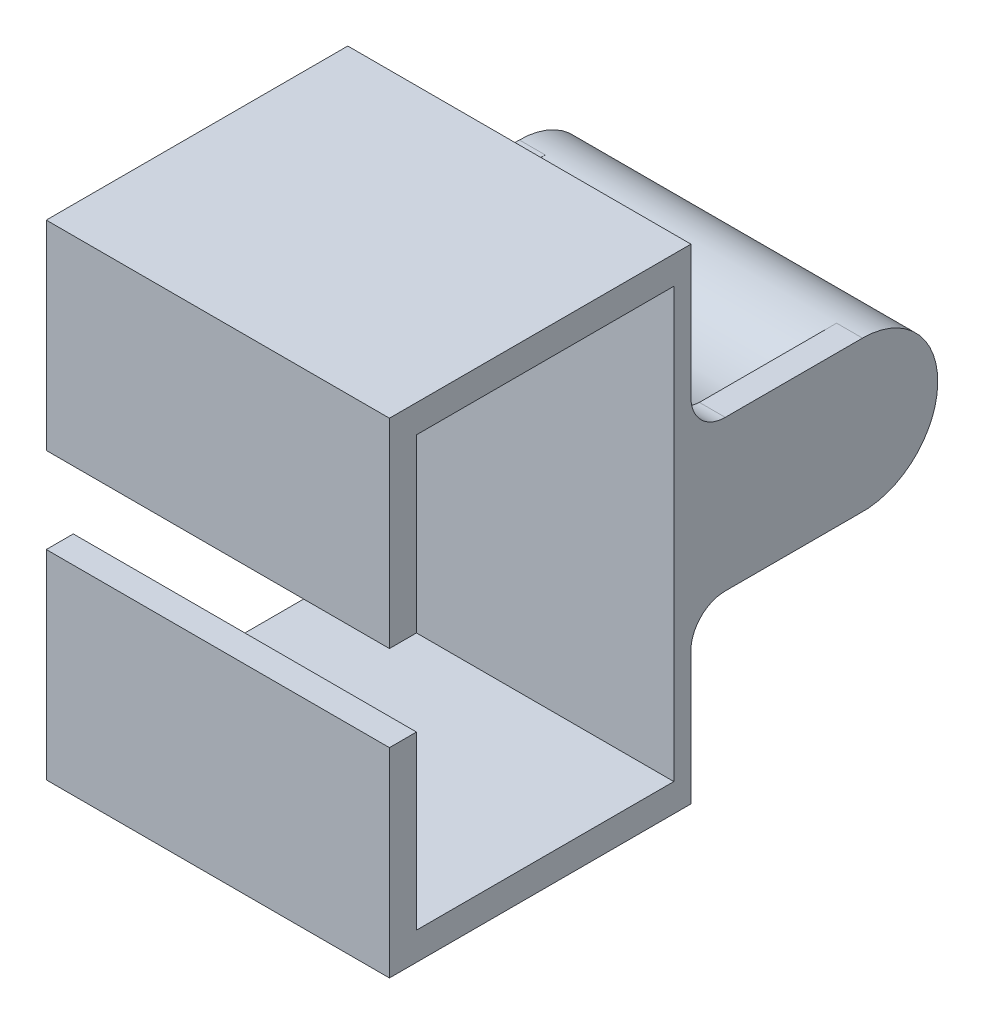
SolidWorks part; units mm, degrees
material "ASTM A36 Steel"
ref_plane "Front Plane" through (0, 0, 0) normal (1, 0, 0) x (0, 1, 0)
ref_plane "Top Plane" through (0, 0, 0) normal (0, 0, 1) x (0, 1, 0)
ref_plane "Right Plane" through (0, 0, 0) normal (0, 1, 0) x (-1, 0, 0)
sketch "Sketch1" plane through (0, 0, 0) normal (1, 0, 0) x (0, 1, 0)
  circle A0 centre (0, 0) radius 11.1361
  dimension "D1" = 22.2722
extrude "Boss-Extrude1" add sketch "Sketch1" along normal blind 50.8 contours A0
sketch "Sketch2" plane through (0, 0, 0) normal (-1, 0, 0) x (0, -1, 0)
  line L0 (12.2437, 0) -> (-12.2437, 0) construction
  line L1 (-11.1361, 0) -> (11.1252, 0)
  line L2 (-11.1361, 0) -> (-11.1361, 25.4)
  line L3 (-11.1361, 25.4) -> (11.1252, 25.4)
  line L4 (11.1252, 0) -> (11.1252, 25.4)
  circle A0 centre (0, 0) radius 11.1361 construction
  dimension "D1" = 25.4
extrude "Boss-Extrude2" add sketch "Sketch2" against normal blind 3.8346 contours L2 L3 L4 L1
sketch "Sketch3" plane through (0, 0, 0) normal (1, 0, 0) x (0, 1, 0)
  line L0 (0, -27.94) -> (0, 27.94) construction
  line L1 (-31.75, 25.4) -> (31.75, 25.4)
  line L2 (-31.75, 25.4) -> (-31.75, 27.9309)
  line L3 (-31.75, 27.9309) -> (31.75, 27.9309)
  line L4 (31.75, 25.4) -> (31.75, 27.9309)
  line L5 (11.1361, 25.4) -> (-11.1252, 25.4) construction
  point P4 (0, 25.4)
  dimension "D1" = 63.5
  dimension "D2" = 2.5309
extrude "Boss-Extrude3" add sketch "Sketch3" along normal blind 50.8
sketch "Sketch4" plane through (0, 0, 0) normal (1, 0, 0) x (0, 1, 0)
  line L0 (31.75, 27.9309) -> (-31.75, 27.9309) construction
  line L1 (-31.75, 25.4) -> (-35.8829, 25.4)
  line L2 (-31.75, 25.4) -> (-31.75, 66.0309)
  line L3 (-31.75, 66.0309) -> (-35.8829, 66.0309)
  line L4 (-35.8829, 25.4) -> (-35.8829, 66.0309)
  line L5 (31.75, 25.4) -> (35.8829, 25.4)
  line L6 (31.75, 25.4) -> (31.75, 66.0309)
  line L7 (31.75, 66.0309) -> (35.8829, 66.0309)
  line L8 (35.8829, 25.4) -> (35.8829, 66.0309)
  dimension "D2" = 38.1
extrude "Boss-Extrude4" add sketch "Sketch4" along normal blind 50.8
sketch "Sketch5" plane through (0, 0, 0) normal (1, 0, 0) x (0, 1, 0)
  line L1 (-35.8829, 66.0309) -> (-6.35, 66.0309)
  line L2 (-35.8829, 66.0309) -> (-35.8829, 70.0326)
  line L3 (-35.8829, 70.0326) -> (-6.35, 70.0326)
  line L4 (-6.35, 66.0309) -> (-6.35, 70.0326)
  line L5 (35.8829, 66.0309) -> (6.35, 66.0309)
  line L6 (35.8829, 66.0309) -> (35.8829, 70.0326)
  line L7 (35.8829, 70.0326) -> (6.35, 70.0326)
  line L8 (6.35, 66.0309) -> (6.35, 70.0326)
  dimension "D2" = 25.4
  dimension "D3" = 12.7
extrude "Boss-Extrude5" add sketch "Sketch5" along normal blind 50.8
sketch "Sketch6" plane through (50.8, 0, 0) normal (1, 0, 0) x (0, 1, 0)
  line L0 (27.94, 0) -> (-27.94, 0) construction
  line L1 (-11.1252, 25.4) -> (11.1361, 25.4)
  line L2 (-11.1252, 25.4) -> (-11.1252, 0)
  line L3 (-11.1252, 0) -> (11.1361, 0)
  line L4 (11.1361, 25.4) -> (11.1361, 0)
  arc A0 (11.1361, 0) -> (-11.1252, 0.4931) centre (0, 0) ccw construction
extrude "Boss-Extrude6" add sketch "Sketch6" against normal blind 3.8346
fillet "Fillet2" radius 5.08 6 edges at (1.9173, 11.1361, 25.4) (48.8827, 11.1361, 25.4) (48.8827, -11.1252, 25.4) (46.9654, 0.0055, 25.4) (3.8346, 0.0055, 25.4) (1.9173, -11.1252, 25.4)
equation "\"SAFETY_FAC\"= 4'Given Safety Factor"
equation "\"LOAD\"= 600'Chosen Applied Load (lbf)"
equation "\"LENGTH_A\"= 1in'Chosen Length for Feature A (in)"
equation "\"STRENGTH\"= 36259.4'ASTM A36 Steel Yield Strenght (psi)"
equation "\"DIAMETER_A\"= 2 * ( ( 4 * \"SAFETY_FAC\" * \"LOAD\" * \"LENGTH_A\" ) / ( PI * \"STRENGTH\" ) ) ^ ( 1 / 3 )'Calculated Diameter of Feature A (in)"
equation "\"THICKNESS_B\"= ( \"LOAD\" * 8 ) / ( \"STRENGTH\" * \"DIAMETER_A\" )'Calculated Thickness of Feature B (in)"
equation "\"LENGTH_C\"= 2.5'Found Length based on Given Rigid T-beam Dimensions (in)"
equation "\"PRIMARY_THICKNESS\"= 2'Chosen Thickness of the primary section (in_"
equation "\"HEIGHT_C\"= ( ( ( 3 * \"LOAD\" * \"LENGTH_C\" * \"SAFETY_FAC\" ) / ( \"PRIMARY_THICKNESS\" * \"STRENGTH\" ) ) ^ ( 1 / 2 ) ) / 5'Calculated Height of Feature C (in)"
equation "\"LOAD_DISTANCE_D\"= \"LENGTH_C\" / 2'Calculated Distance of Load Applied to Feature D (in)"
equation "\"HEIGHT_D\"= 1.5'Found Height based on the GIven Rigid T-beam Dimensions (in)"
equation "\"LENGTH_D\"= ( ( ( 12 * \"LOAD\" * \"LOAD_DISTANCE_D\" * \"SAFETY_FAC\" ) / ( \"HEIGHT_D\" * \"STRENGTH\" ) ) ^ ( 1 / 2 ) ) / 5'Calculated Length of Feature D (in)"
equation "\"LENGTH_E\"= 1'Found Length for Feature E on given Rigid T-Beam Dimensions (in)"
equation "\"HEIGHT_E\"= ( ( ( 3 * \"LENGTH_E\" * \"LOAD\" * \"SAFETY_FAC\" ) / ( \"PRIMARY_THICKNESS\" * \"STRENGTH\" ) ) ^ ( 1 / 2 ) ) / 2'Calculated height of Feature E (in)"
equation "\"D1@Sketch1\"=\"DIAMETER_A\""
equation "\"D1@Boss-Extrude1\"=\"PRIMARY_THICKNESS\""
equation "\"D1@Boss-Extrude2\"=\"THICKNESS_B\""
equation "\"D1@Sketch3\"=\"LENGTH_C\""
equation "\"D2@Sketch3\"=\"HEIGHT_C\""
equation "\"D1@Boss-Extrude3\"=\"PRIMARY_THICKNESS\""
equation "\"D2@Sketch4\"=\"HEIGHT_D\""
equation "\"D1@Sketch4\"=\"LENGTH_D\""
equation "\"D1@Boss-Extrude4\"=\"PRIMARY_THICKNESS\""
equation "\"D1@Sketch5\"=\"HEIGHT_E\""
equation "\"D2@Sketch5\"=\"LENGTH_E\""
equation "\"D1@Boss-Extrude5\"=\"PRIMARY_THICKNESS\""
equation "\"D1@Boss-Extrude6\"=\"THICKNESS_B\""
